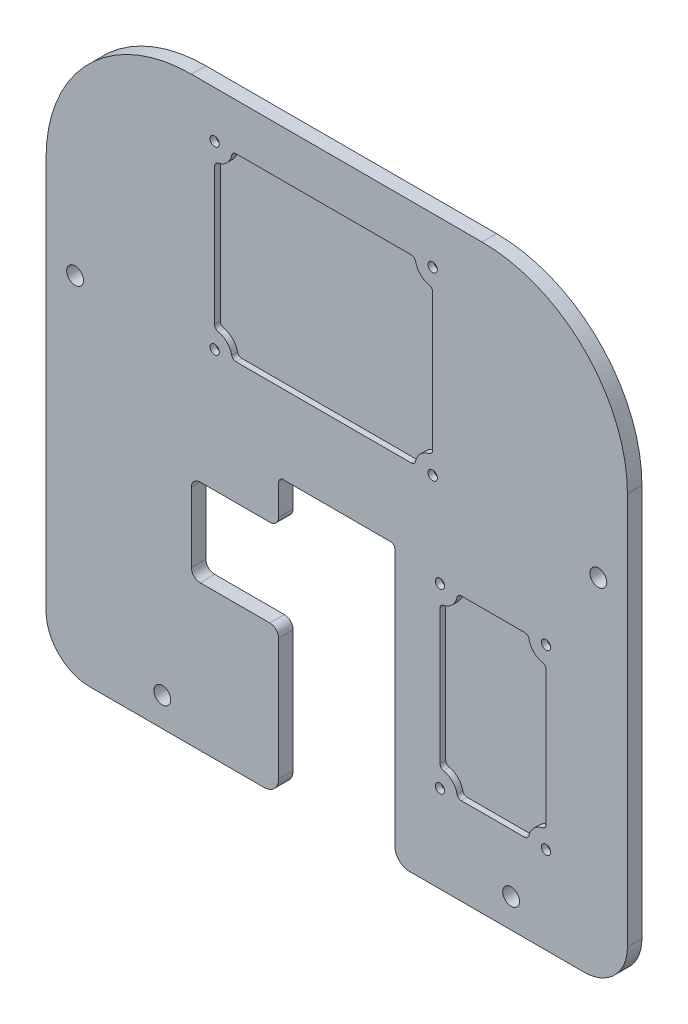
SolidWorks part; units mm, degrees
material "ｱｸﾘﾙ (中-上級の耐衝撃性)"
ref_plane "正面" through (0, 0, 0) normal (0, 0, 1) x (1, 0, 0)
ref_plane "平面" through (0, 0, 0) normal (0, 1, 0) x (1, 0, 0)
ref_plane "右側面" through (0, 0, 0) normal (1, 0, 0) x (0, 0, -1)
sketch "ｽｹｯﾁ1" plane through (0, 0, 0) normal (0, 0, 1) x (1, 0, 0)
  line L1 (-100, 110) -> (100, 110)
  line L2 (-100, 110) -> (-100, -90)
  line L3 (-100, -90) -> (100, -90)
  line L4 (100, 110) -> (100, -90)
  dimension "D1" = 200
  dimension "D2" = 90
  dimension "D3" = 100
  dimension "D4" = 200
extrude "ﾎﾞｽ - 押し出し1" add sketch "ｽｹｯﾁ1" along normal blind 5
sketch "ｽｹｯﾁ2" plane through (0, 0, 5) normal (0, 0, 1) x (1, 0, 0)
  line L0 (-100, -90) -> (100, -90) construction
  line L1 (-20, 5) -> (20, 5)
  line L2 (-20, 5) -> (-20, -90)
  line L3 (-20, -90) -> (20, -90)
  line L4 (20, 5) -> (20, -90)
  line L5 (-100, 110) -> (-100, -90) construction
  dimension "D1" = 40
  dimension "D2" = 80
  dimension "D3" = 95
extrude "ｶｯﾄ - 押し出し1" cut sketch "ｽｹｯﾁ2" against normal through all
fillet "ﾌｨﾚｯﾄ1" radius 50 2 edges at (100, 110, 2.5) (-100, 110, 2.5)
fillet "ﾌｨﾚｯﾄ2" radius 1.5 2 edges at (20, 5, 2.5) (-20, 5, 2.5)
sketch "ｽｹｯﾁ3" plane through (0, 0, 0) normal (0, 0, -1) x (-1, 0, 0)
  line L0 (20, 3.5) -> (20, -90) construction
  line L1 (20, -10) -> (50, -10)
  line L2 (20, -10) -> (20, -40)
  line L3 (20, -40) -> (50, -40)
  line L4 (50, -10) -> (50, -40)
  line L5 (100, -90) -> (20, -90) construction
  dimension "D1" = 30
  dimension "D2" = 30
  dimension "D3" = 50
extrude "ｶｯﾄ - 押し出し2" cut sketch "ｽｹｯﾁ3" against normal blind 10
fillet "ﾌｨﾚｯﾄ3" radius 3 4 edges at (-20, -40, 2.5) (-50, -40, 2.5) (-50, -10, 2.5) (-20, -10, 2.5)
sketch "ｽｹｯﾁ4" plane through (0, 0, 5) normal (0, 0, 1) x (1, 0, 0)
  line L1 (-34.6515, 94) -> (25.6515, 94)
  line L2 (-42, 86.6515) -> (-42, 39.3485)
  line L3 (-34.6515, 32) -> (25.6515, 32)
  line L4 (33, 86.6515) -> (33, 39.3485)
  circle A0 centre (-42, 94) radius 1.6 construction
  circle A1 centre (33, 94) radius 1.6 construction
  circle A2 centre (-42, 32) radius 1.6 construction
  circle A3 centre (33, 32) radius 1.6 construction
  circle A4 centre (-42, 94) radius 1.6
  circle A5 centre (33, 94) radius 1.6
  circle A6 centre (-42, 32) radius 1.6
  circle A7 centre (33, 32) radius 1.6
  arc A8 (-36.1212, 92.8) -> (-40.8, 88.1212) centre (-42, 94) cw
  arc A9 (-36.1212, 33.2) -> (-40.8, 37.8788) centre (-42, 32) ccw
  arc A10 (31.8, 37.8788) -> (27.1212, 33.2) centre (33, 32) ccw
  arc A11 (27.1212, 92.8) -> (31.8, 88.1212) centre (33, 94) ccw
  arc A12 (-36.1212, 92.8) -> (-34.6515, 94) centre (-34.6515, 92.5) cw
  arc A13 (-42, 86.6515) -> (-40.8, 88.1212) centre (-40.5, 86.6515) cw
  arc A14 (-40.8, 37.8788) -> (-42, 39.3485) centre (-40.5, 39.3485) cw
  arc A15 (-34.6515, 32) -> (-36.1212, 33.2) centre (-34.6515, 33.5) cw
  arc A16 (27.1212, 33.2) -> (25.6515, 32) centre (25.6515, 33.5) cw
  arc A17 (33, 39.3485) -> (31.8, 37.8788) centre (31.5, 39.3485) cw
  arc A18 (33, 86.6515) -> (31.8, 88.1212) centre (31.5, 86.6515) ccw
  arc A19 (25.6515, 94) -> (27.1212, 92.8) centre (25.6515, 92.5) cw
  dimension "D1" = 6
  dimension "D2" = 6
  dimension "D3" = 6
  dimension "D4" = 6
  dimension "D5" = 1.5
  dimension "D6" = 1.5
  dimension "D7" = 1.5
  dimension "D8" = 1.5
  dimension "D9" = 1.5
  dimension "D10" = 1.5
  dimension "D11" = 1.5
  dimension "D12" = 1.5
hole_wizard "M3x0.5 ねじ穴用ねじ下穴ﾄﾞﾘﾙ2" positions "ｽｹｯﾁ6" profile "ｽｹｯﾁ5" hole size "M3x0.5" standard "ANSIﾒｰﾄﾙ" end condition through all
sketch "ｽｹｯﾁ6" plane through (0, 0, 5) normal (0, 0, 1) x (1, 0, 0)
  point P1 (-42, 94)
  point P4 (33, 94)
  point P7 (-42, 32)
  point P10 (33, 32)
sketch "ｽｹｯﾁ5" plane through (-42, 94, 5) normal (1, 0, 0) x (0, -1, 0)
  line L0 (0, 0) -> (0, 5)
  line L1 (0, 5) -> (1.25, 5)
  line L2 (1.25, 5) -> (1.25, 0)
  line L5 (1.25, 0) -> (0, 0)
  line L11 (0, -6.35) -> (0, 107.95) construction
  dimension "通し穴の直径" = 2.5
  dimension "通し穴の深さ" = 5
sketch "ｽｹｯﾁ7" plane through (0, 0, 5) normal (0, 0, 1) x (1, 0, 0)
  line L1 (64.6515, -60) -> (42.8485, -60)
  line L2 (72, -52.6515) -> (72, -6.3485)
  line L3 (64.6515, 1) -> (42.8485, 1)
  line L4 (35.5, -52.6515) -> (35.5, -6.3485)
  circle A0 centre (35.5, 1) radius 1.6 construction
  circle A1 centre (72, 1) radius 1.6 construction
  circle A2 centre (35.5, -60) radius 1.6 construction
  circle A3 centre (72, -60) radius 1.6 construction
  circle A4 centre (35.5, 1) radius 1.6
  circle A5 centre (72, 1) radius 1.6
  circle A6 centre (35.5, -60) radius 1.6
  circle A7 centre (72, -60) radius 1.6
  arc A8 (41.3788, -0.2) -> (36.7, -4.8788) centre (35.5, 1) cw
  arc A9 (41.3788, -58.8) -> (36.7, -54.1212) centre (35.5, -60) ccw
  arc A10 (70.8, -54.1212) -> (66.1212, -58.8) centre (72, -60) ccw
  arc A11 (66.1212, -0.2) -> (70.8, -4.8788) centre (72, 1) ccw
  arc A12 (41.3788, -0.2) -> (42.8485, 1) centre (42.8485, -0.5) cw
  arc A13 (36.7, -4.8788) -> (35.5, -6.3485) centre (37, -6.3485) ccw
  arc A14 (36.7, -54.1212) -> (35.5, -52.6515) centre (37, -52.6515) cw
  arc A15 (42.8485, -60) -> (41.3788, -58.8) centre (42.8485, -58.5) cw
  arc A16 (66.1212, -58.8) -> (64.6515, -60) centre (64.6515, -58.5) cw
  arc A17 (72, -52.6515) -> (70.8, -54.1212) centre (70.5, -52.6515) cw
  arc A18 (72, -6.3485) -> (70.8, -4.8788) centre (70.5, -6.3485) ccw
  arc A19 (64.6515, 1) -> (66.1212, -0.2) centre (64.6515, -0.5) cw
  dimension "D1" = 6
  dimension "D2" = 6
  dimension "D3" = 6
  dimension "D4" = 6
  dimension "D5" = 1.5
  dimension "D6" = 1.5
  dimension "D7" = 1.5
  dimension "D8" = 1.5
  dimension "D9" = 1.5
  dimension "D10" = 1.5
  dimension "D11" = 1.5
  dimension "D12" = 1.5
hole_wizard "M3x0.5 ねじ穴用ねじ下穴ﾄﾞﾘﾙ1" positions "ｽｹｯﾁ9" profile "ｽｹｯﾁ8" hole size "M3x0.5" standard "ANSIﾒｰﾄﾙ" end condition through all
sketch "ｽｹｯﾁ9" plane through (0, 0, 5) normal (0, 0, 1) x (1, 0, 0)
  point P1 (35.5, 1)
  point P4 (72, 1)
  point P7 (35.5, -60)
  point P10 (72, -60)
sketch "ｽｹｯﾁ8" plane through (35.5, 1, 5) normal (1, 0, 0) x (0, -1, 0)
  line L0 (0, 0) -> (0, 5)
  line L1 (0, 5) -> (1.25, 5)
  line L2 (1.25, 5) -> (1.25, 0)
  line L5 (1.25, 0) -> (0, 0)
  line L11 (0, -6.35) -> (0, 107.95) construction
  dimension "通し穴の直径" = 2.5
  dimension "通し穴の深さ" = 5
fillet "ﾌｨﾚｯﾄ4" radius 15 2 edges at (100, -90, 2.5) (-100, -90, 2.5)
fillet "ﾌｨﾚｯﾄ5" radius 5 2 edges at (-20, -90, 2.5) (20, -90, 2.5)
hole_wizard "M5 すきま穴1" positions "ｽｹｯﾁ11" profile "ｽｹｯﾁ10" hole size "M5" standard "ANSIﾒｰﾄﾙ" end condition through all
sketch "ｽｹｯﾁ11" plane through (0, 0, 0) normal (0, 0, -1) x (-1, 0, 0)
  line L0 (-25, -90) -> (-85, -90) construction
  line L1 (85, -90) -> (25, -90) construction
  line L2 (-100, -75) -> (-100, 60) construction
  line L3 (100, 60) -> (100, -75) construction
  point P0 (-60, -80)
  point P1 (60, -80)
  point P3 (-90, 30)
  point P5 (90, 30)
  dimension "D1" = 10
  dimension "D2" = 10
  dimension "D3" = 40
  dimension "D4" = 40
  dimension "D5" = 10
  dimension "D6" = 10
  dimension "D7" = 120
  dimension "D8" = 120
sketch "ｽｹｯﾁ10" plane through (60, -80, 0) normal (1, 0, 0) x (0, 1, 0)
  line L0 (0, 0) -> (0, 5)
  line L1 (0, 5) -> (2.9, 5)
  line L2 (2.9, 5) -> (2.9, 0)
  line L5 (2.9, 0) -> (0, 0)
  line L11 (0, -6.35) -> (0, 107.95) construction
  dimension "通し穴の直径" = 5.8
  dimension "通し穴の深さ" = 5
extrude "ｶｯﾄ - 押し出し3" cut sketch "ｽｹｯﾁ4" against normal blind 2
extrude "ｶｯﾄ - 押し出し4" cut sketch "ｽｹｯﾁ7" against normal blind 2
